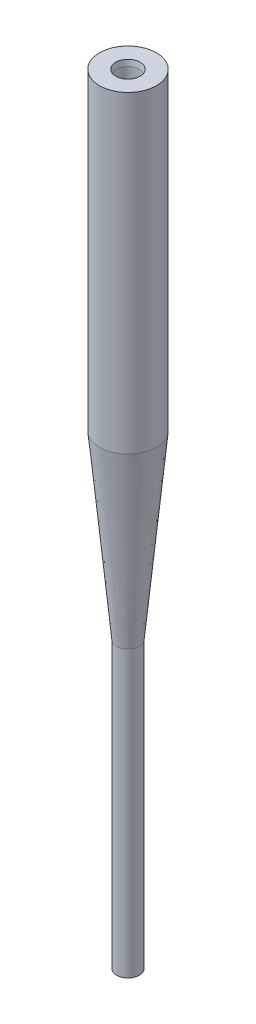
SolidWorks part; units mm, degrees
ref_plane "Front" through (0, 0, 0) normal (0, 0, 1) x (1, 0, 0)
ref_plane "Top" through (0, 0, 0) normal (0, 1, 0) x (1, 0, 0)
ref_plane "Right" through (0, 0, 0) normal (1, 0, 0) x (0, 0, -1)
sketch "Sketch1" plane through (0, 0, 0) normal (0, 0, 1) x (1, 0, 0)
  line L0 (0, 0) -> (0, 95.25) construction
  line L1 (0, 95.25) -> (15.875, 95.25)
  line L2 (15.875, 95.25) -> (15.875, 0)
  line L3 (15.875, 0) -> (6.3529, 0)
  line L4 (6.3529, 0) -> (6.3529, -38.8366)
  line L5 (6.3529, -38.8366) -> (7.9248, -44.1812)
  line L6 (7.9248, -44.1812) -> (7.9248, -52.07)
  line L7 (7.9248, -52.07) -> (0, -52.07)
  line L8 (0, -52.07) -> (0, 0) construction
  line L9 (0, 95.25) -> (0, -52.07)
  dimension "D1" = 31.75
  dimension "D2" = 95.25
  dimension "D3" = 15.8496
  dimension "D4" = 147.32
revolve "Revolve1" add sketch "Sketch1" angle 360 about L9
sketch "Sketch2" plane through (0, 0, 0) normal (0, 0, 1) x (1, 0, 0)
  line L0 (0, -52.07) -> (0, -188.87)
  line L1 (0, -188.87) -> (2, -188.87)
  line L2 (2, -188.87) -> (2, -138.87)
  line L3 (2, -138.87) -> (5, -107.07)
  line L4 (5, -107.07) -> (5, -52.07)
  line L5 (7.9248, -52.07) -> (0, -52.07) construction
  line L6 (5, -52.07) -> (0, -52.07)
  dimension "D1" = 136.8
  dimension "D2" = 55
  dimension "D3" = 50
  dimension "D4" = 2
  dimension "D5" = 5
sketch "Sketch3" plane through (0, -52.07, 0) normal (0, -1, 0) x (1, 0, 0)
  circle A0 centre (0, 0) radius 2.8067
  dimension "D1" = 5.6134
extrude "Cut-Extrude1" cut sketch "Sketch3" against normal blind 12
chamfer "Chamfer1" distance 0.4 angle 70 1 edges at (2.8067, -52.07, 0)
revolve "Revolve2" add sketch "Sketch2" angle 360 about L0
delete or keep bodies "Body-Delete/Keep 1" type keep bodies bodies 102
sketch "Sketch4" plane through (0, -52.07, 0) normal (0, 1, 0) x (1, 0, 0)
  circle A0 centre (0, 0) radius 2
  dimension "D1" = 4
extrude "Cut-Extrude2" cut sketch "Sketch4" against normal blind 6
chamfer "Chamfer2" distance 1 angle 8 1 edges at (-2, -52.07, 0)
